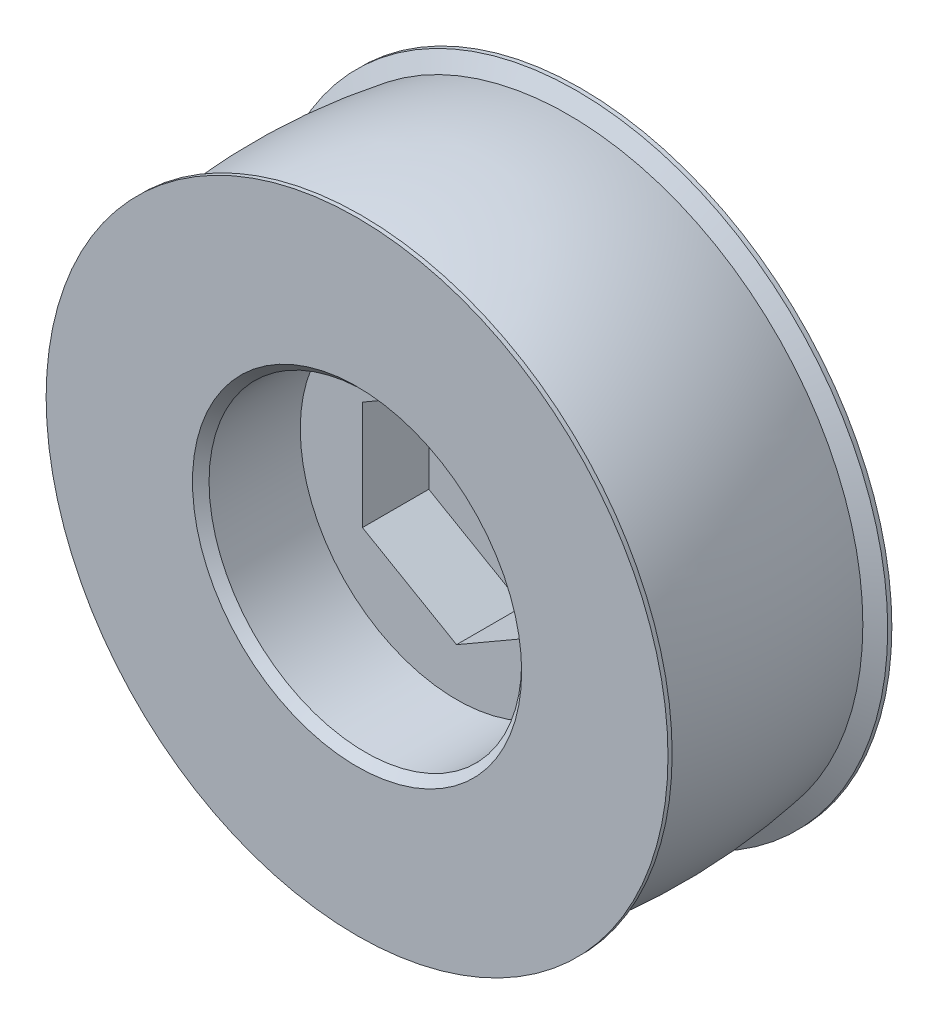
SolidWorks part; units mm, degrees
ref_plane "Plan de face" through (0, 0, 0) normal (0, 0, 1) x (1, 0, 0)
ref_plane "Plan de dessus" through (0, 0, 0) normal (0, 1, 0) x (1, 0, 0)
ref_plane "Plan de droite" through (0, 0, 0) normal (1, 0, 0) x (0, 0, -1)
sketch "Esquisse1" plane through (0, 0, 0) normal (0, 0, 1) x (1, 0, 0)
  circle A0 centre (0, 0) radius 3.25
  circle A1 centre (0, 0) radius 37.5
  dimension "D1" = 75
  dimension "D2" = 6.5
extrude "Boss.-Extru.1" add sketch "Esquisse1" along normal blind 15
sketch "Esquisse2" plane through (0, 0, 15) normal (0, 0, 1) x (1, 0, 0)
  circle A0 centre (0, 0) radius 37.5
  circle A1 centre (0, 0) radius 18.85
  circle A2 centre (0, 0) radius 37.5 construction
  dimension "D1" = 37.7
extrude "Boss.-Extru.2" add sketch "Esquisse2" along normal blind 12
sketch "Esquisse9" plane through (0, 0, 15) normal (0, 0, 1) x (1, 0, 0)
  line L0 (0, 0) -> (0, 26.2117) construction
  line L1 (11.35, -6.5529) -> (11.35, 6.5529)
  line L2 (11.35, 6.5529) -> (0, 13.1059)
  line L3 (0, 13.1059) -> (-11.35, 6.5529)
  line L4 (-11.35, 6.5529) -> (-11.35, -6.5529)
  line L5 (-11.35, -6.5529) -> (0, -13.1059)
  line L6 (0, -13.1059) -> (11.35, -6.5529)
  circle A0 centre (0, 0) radius 11.35 construction
  dimension "D1" = 22.7
extrude "Enlèv. mat.-Extru.9" cut sketch "Esquisse9" against normal offset from surface (8 mm away) 7 up to face at (37.5, 0, 0)
chamfer "Chanfrein1" distance 1 angle 45 1 edges at (18.85, 0, 27)
sketch "Esquisse10" plane through (0, 0, 0) normal (1, 0, 0) x (0, 0, -1)
  line L0 (-26.5, 37.5) -> (-0.5, 37.5)
  line L1 (0, 37.5) -> (-27, 37.5) construction
  line L2 (-0.5, 37.5) -> (-1.5, 35.5)
  line L3 (-1.5, 35.5) -> (-25.5, 35.5) construction
  line L4 (-25.5, 35.5) -> (-26.5, 37.5)
  line L5 (-19.6787, 36.5) -> (-7.7815, 36.5) construction
  line L6 (0, 0) -> (-50.6564, 0) construction
  arc A0 (-25.5, 35.5) -> (-1.5, 35.5) centre (-13.5, -36) cw
  dimension "D6" = 1
  dimension "D1" = 2
  dimension "D2" = 0.5
  dimension "D3" = 0.5
  dimension "D4" = 1
  dimension "D5" = 1
revolve "Enlèvement de matière-Révolution1" cut sketch "Esquisse10" angle 360 about L6
sketch "Esquisse11" plane through (0, 0, 0) normal (0, 0, -1) x (-1, 0, 0)
  line L0 (0, 0) -> (32.476, 18.75) construction
  line L1 (0, 0) -> (-32.476, 18.75) construction
  line L2 (0, 0) -> (0, -37.5) construction
  circle A0 centre (0, 0) radius 37.5 construction
  circle A1 centre (-6.9282, 4) radius 1.25
  circle A2 centre (6.9282, 4) radius 1.25
  circle A3 centre (0, -8) radius 1.25
  circle A4 centre (0, 0) radius 8 construction
  dimension "D3" = 2.5
  dimension "D4" = 16
  dimension "D1" = 120
  dimension "D2" = 120
extrude "Enlèv. mat.-Extru.10" cut sketch "Esquisse11" against normal through all
sketch "Esquisse12" plane through (0, 0, 0) normal (0, 0, -1) x (-1, 0, 0)
  circle A0 centre (-6.9282, 4) radius 4.25
  circle A1 centre (6.9282, 4) radius 4.25
  circle A2 centre (0, -8) radius 4.25
  dimension "D1" = 8.5
extrude "Enlèv. mat.-Extru.11" cut sketch "Esquisse12" against normal blind 4
